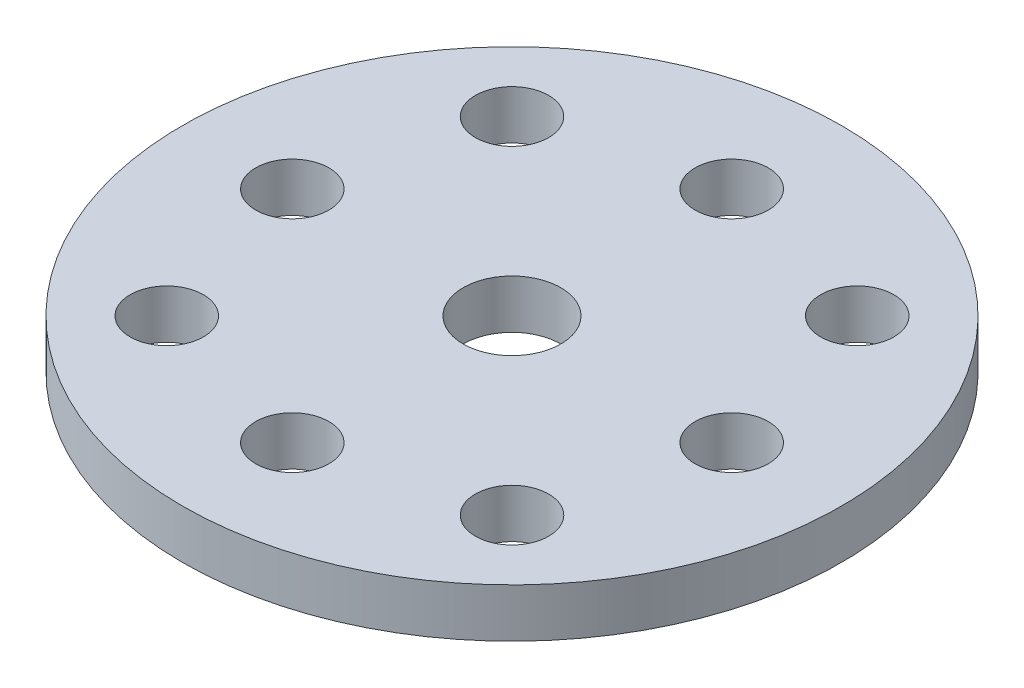
SolidWorks part; units mm, degrees
ref_plane "Front Plane" through (0, 0, 0) normal (0, 0, 1) x (1, 0, 0)
ref_plane "Top Plane" through (0, 0, 0) normal (0, 1, 0) x (1, 0, 0)
ref_plane "Right Plane" through (0, 0, 0) normal (1, 0, 0) x (0, 0, -1)
sketch "Sketch1" plane through (0, 0, 0) normal (0, 1, 0) x (1, 0, 0)
  circle A0 centre (0, 0) radius 13.5
  dimension "D1" = 27
extrude "Boss-Extrude1" add sketch "Sketch1" along normal blind 2
sketch "Sketch2" plane through (0, 2, 0) normal (0, 1, 0) x (1, 0, 0)
  circle A0 centre (0, 0) radius 2
  dimension "D1" = 4
sketch "Sketch4" plane through (0, 0, 0) normal (0, -1, 0) x (1, 0, 0)
  line L0 (0, 0) -> (-10, 0)
  line L1 (0, 0) -> (-7.0711, -7.0711)
  circle A0 centre (0, 0) radius 9 construction
  circle A1 centre (-9, 0) radius 1.5
  circle A2 centre (0, 0) radius 10 construction
  circle A3 centre (-7.0711, -7.0711) radius 1.5
  dimension "D1" = 18
  dimension "D2" = 3
  dimension "D3" = 20
  dimension "D4" = 3
  dimension "D5" = 45
extrude "Cut-Extrude1" cut sketch "Sketch4" against normal through all
pattern_circular "CirPattern1" count 4 over 360 about axis through (0, 0, 0) along (0, 1, 0) of "Cut-Extrude1"
extrude "Cut-Extrude2" cut sketch "Sketch2" against normal through all
